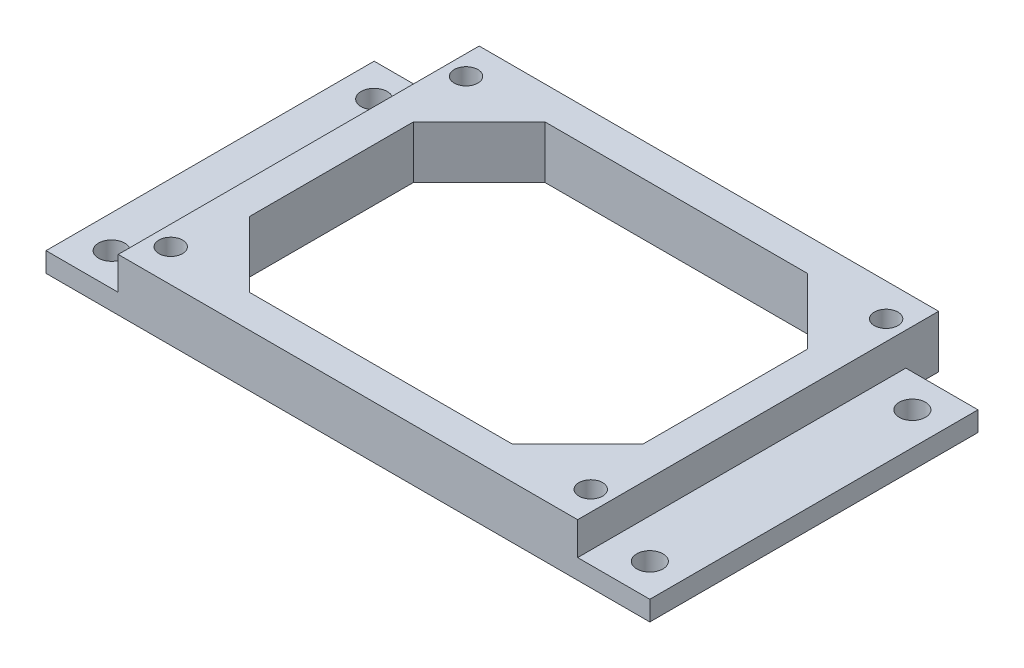
SolidWorks part; units mm, degrees
ref_plane "Front Plane" through (0, 0, 0) normal (0, 0, 1) x (1, 0, 0)
ref_plane "Top Plane" through (0, 0, 0) normal (0, 1, 0) x (1, 0, 0)
ref_plane "Right Plane" through (0, 0, 0) normal (1, 0, 0) x (0, 0, -1)
sketch "Sketch1" plane through (0, 0, 0) normal (0, 1, 0) x (1, 0, 0)
  line L1 (-35, -25) -> (35, -25)
  line L2 (-35, -25) -> (-35, 25)
  line L3 (-35, 25) -> (35, 25)
  line L4 (35, -25) -> (35, 25)
  line L5 (-35, -25) -> (35, 25) construction
  line L6 (-35, 25) -> (35, -25) construction
  point P0 (0, 0)
  dimension "D1" = 70
  dimension "D2" = 50
extrude "Boss-Extrude1" add sketch "Sketch1" along normal blind 5
sketch "Sketch2" plane through (0, 0, 0) normal (0, -1, 0) x (1, 0, 0)
  line L0 (-35, 25) -> (35, 25) construction
  line L1 (-46, -25) -> (46, -25)
  line L2 (-46, -25) -> (-46, 25)
  line L3 (-46, 25) -> (46, 25)
  line L4 (46, -25) -> (46, 25)
  line L5 (-46, -25) -> (46, 25) construction
  line L6 (-46, 25) -> (46, -25) construction
  point P0 (0, 0)
  dimension "D1" = 92
extrude "Boss-Extrude2" add sketch "Sketch2" along normal blind 3
sketch "Sketch3" plane through (0, 0, 0) normal (0, 1, 0) x (1, 0, 0)
  line L1 (-40.5, -15.25) -> (40.5, -15.25)
  line L2 (-40.5, -15.25) -> (-40.5, 15.25)
  line L3 (-40.5, 15.25) -> (40.5, 15.25)
  line L4 (40.5, -15.25) -> (40.5, 15.25)
  line L5 (-40.5, -15.25) -> (40.5, 15.25) construction
  line L6 (-40.5, 15.25) -> (40.5, -15.25) construction
  point P0 (0, 0)
  dimension "D1" = 30.5
  dimension "D2" = 81
hole_wizard "M3 Clearance Hole1" positions "Sketch7" profile "Sketch8" hole size "M3" standard "ANSI Metric"
sketch "Sketch7" plane through (0, 0, 0) normal (0, 1, 0) x (1, 0, 0)
  line L0 (-46, 25) -> (-35, 25) construction
  line L1 (35, 25) -> (46, 25) construction
  line L2 (46, -25) -> (35, -25) construction
  line L3 (-35, -25) -> (-46, -25) construction
  line L4 (-46, -25) -> (-46, 25) construction
  line L5 (46, 25) -> (46, -25) construction
  point P0 (-41, 20)
  point P2 (-41, -20)
  point P4 (41, 20)
  point P6 (41, -20)
  dimension "D1" = 5
  dimension "D2" = 5
  dimension "D3" = 5
  dimension "D4" = 5
  dimension "D5" = 5
  dimension "D6" = 5
sketch "Sketch8" plane through (-41, 0, -20) normal (1, 0, 0) x (0, 0, 1)
  line L0 (0, 0) -> (0, 11.2017)
  line L1 (0, 11.2017) -> (2, 10)
  line L2 (2, 10) -> (2, 0)
  line L5 (2, 0) -> (0, 0)
  line L10 (0, 11.2017) -> (-2, 10) construction
  line L11 (0, -6.35) -> (0, 107.95) construction
  dimension "Hole Dia." = 4
  dimension "Hole Depth" = 10
  dimension "Drill Angle" = 118
sketch "Sketch9" plane through (0, 0, -25) normal (0, 0, -1) x (-1, 0, 0)
  line L0 (-35, 5) -> (35, 5) construction
  line L1 (-35, 5) -> (35, 5)
  line L2 (-35, 5) -> (-35, -3)
  line L3 (-35, -3) -> (35, -3)
  line L4 (35, 5) -> (35, -3)
  line L5 (46, -3) -> (-46, -3) construction
  line L6 (-35, 5) -> (-35, 0) construction
  line L7 (35, 5) -> (35, 0) construction
extrude "Boss-Extrude3" add sketch "Sketch9" along normal blind 5
hole_wizard "M3 Clearance Hole3" positions "Sketch10" profile "Sketch11" hole size "M3" standard "ANSI Metric"
sketch "Sketch10" plane through (0, 5, 0) normal (0, 1, 0) x (1, 0, 0)
  line L1 (32, -20) -> (-32, -20)
  line L2 (32, -20) -> (32, 25)
  line L3 (32, 25) -> (-32, 25)
  line L4 (-32, -20) -> (-32, 25)
  line L5 (-35, -25) -> (35, -25) construction
  point P1 (32, -20)
  point P2 (-32, 25)
  point P57 (32, 25)
  point P58 (-32, -20)
  point P60 (0, -20)
  point P63 (0, -25)
  dimension "D1" = 64
  dimension "D2" = 45
  dimension "D3" = 5
sketch "Sketch11" plane through (32, 5, 20) normal (1, 0, 0) x (0, 0, 1)
  line L0 (0, 0) -> (0, 11.0815)
  line L1 (0, 11.0815) -> (1.8, 10)
  line L2 (1.8, 10) -> (1.8, 0)
  line L5 (1.8, 0) -> (0, 0)
  line L10 (0, 11.0815) -> (-1.8, 10) construction
  line L11 (0, -6.35) -> (0, 107.95) construction
  dimension "Hole Dia." = 3.6
  dimension "Hole Depth" = 10
  dimension "Drill Angle" = 118
sketch "Sketch12" plane through (0, 5, 0) normal (0, 1, 0) x (1, 0, 0)
  line L4 (20, -20) -> (30, -10)
  line L5 (-30, -10) -> (-20, -20)
  line L6 (30, 15) -> (20, 25)
  line L7 (-20, 25) -> (-30, 15)
  line L8 (30, -20) -> (30, 25)
  line L9 (30, 25) -> (-30, 25)
  line L10 (-30, 25) -> (-30, -20)
  line L11 (-30, -20) -> (30, -20)
  line L12 (30, -10) -> (30, 15)
  line L13 (20, 25) -> (-20, 25)
  line L14 (-30, 15) -> (-30, -10)
  line L15 (-20, -20) -> (20, -20)
  dimension "D1" = 5
extrude "Cut-Extrude1" cut sketch "Sketch12" against normal through all
equation "\"8`\"=84.8464"
